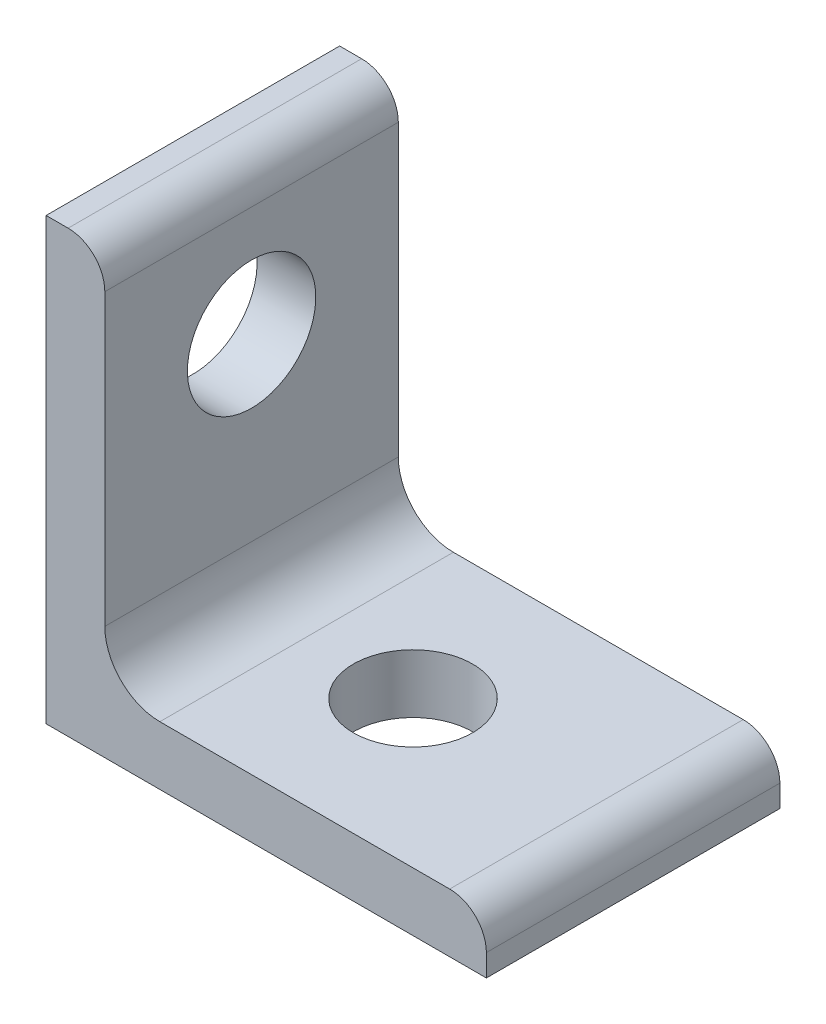
SolidWorks part; units mm, degrees
ref_plane "Front" through (0, 0, 0) normal (0, 0, 1) x (1, 0, 0)
ref_plane "Top" through (0, 0, 0) normal (0, 1, 0) x (1, 0, 0)
ref_plane "Right" through (0, 0, 0) normal (1, 0, 0) x (0, 0, -1)
sketch "Sketch1" plane through (0, 0, 0) normal (0, 0, 1) x (1, 0, 0)
  line L0 (0, 0) -> (0, 38.1)
  line L2 (0, 0) -> (38.1, 0)
  line L3 (34.925, 5.08) -> (9.8425, 5.08)
  line L4 (5.08, 34.925) -> (5.08, 9.8425)
  line L6 (0, 38.1) -> (1.905, 38.1)
  line L7 (38.1, 0) -> (38.1, 1.905)
  arc A0 (5.08, 34.925) -> (1.905, 38.1) centre (1.905, 34.925) ccw
  arc A1 (5.08, 9.8425) -> (9.8425, 5.08) centre (9.8425, 9.8425) ccw
  arc A2 (38.1, 1.905) -> (34.925, 5.08) centre (34.925, 1.905) ccw
extrude "Extrude1" add sketch "Sketch1" along normal blind 25.4
hole_wizard "3/8 Clearance Hole1" positions "Sketch4" profile "Sketch3" hole size "3/8" standard "Ansi Inch" end condition up to next
sketch "Sketch4" plane through (0, 5.08, 0) normal (0, 1, 0) x (-1, 0, 0)
  line L0 (0, 25.4) -> (0, 0) construction
  line L1 (0, 0) -> (-38.1, 0) construction
  point P1 (-19.05, 12.7)
  dimension "D1" = 19.05
  dimension "D2" = 12.7
sketch "Sketch3" plane through (19.05, 5.08, 12.7) normal (1, 0, 0) x (0, 0, 1)
  line L0 (0, 0) -> (0, 5.08)
  line L1 (0, 5.08) -> (5.1587, 5.08)
  line L2 (5.1587, 5.08) -> (5.1587, 0)
  line L5 (5.1587, 0) -> (0, 0)
  line L11 (0, -6.35) -> (0, 107.95) construction
  dimension "Thru Hole Dia." = 10.3175
  dimension "Thru Hole Depth" = 5.08
sketch "Sketch5" plane through (5.08, 0, 0) normal (1, 0, 0) x (0, 0, -1)
  line L0 (0, 38.1) -> (0, 0) construction
  line L2 (-25.4, 0) -> (0, 0) construction
  circle A0 centre (-12.7, 25.4) radius 5.5563
  dimension "D1" = 12.7
  dimension "D2" = 25.4
  dimension "D3" = 11.1125
extrude "Cut-Extrude1" cut sketch "Sketch5" against normal up to next
